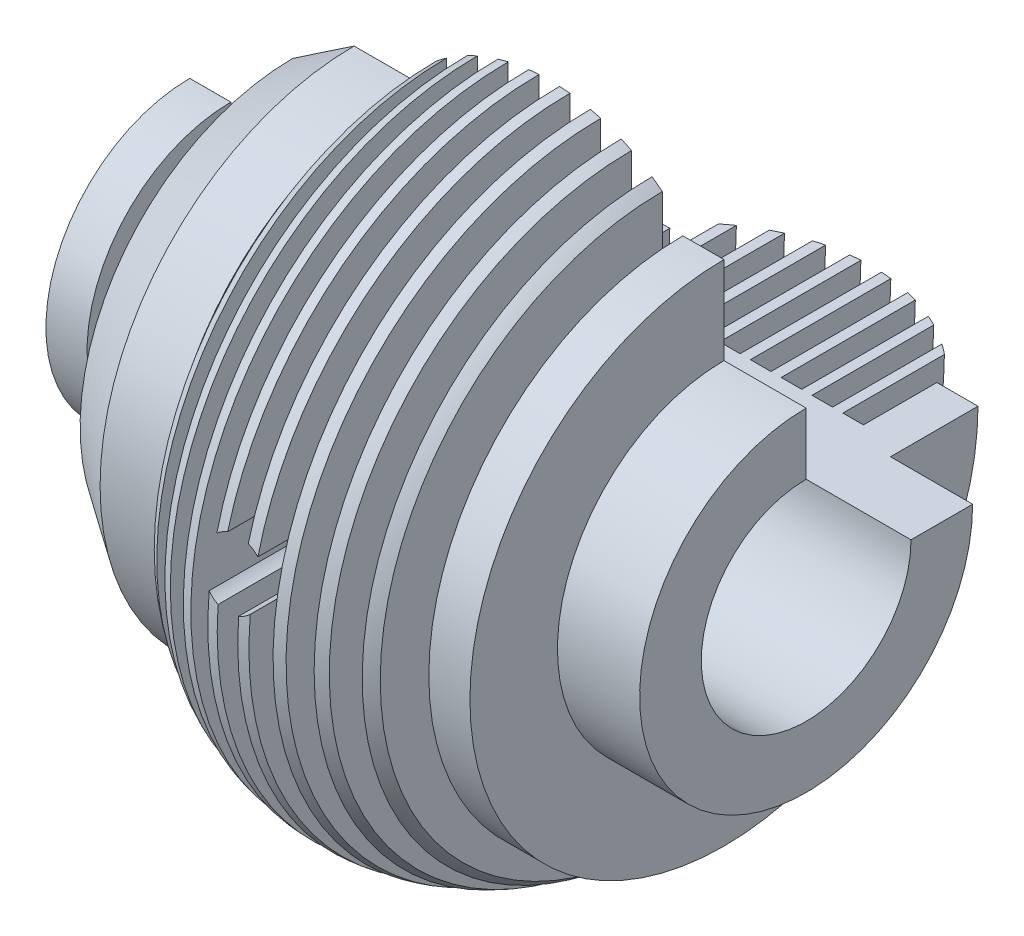
SolidWorks part; units mm, degrees
ref_plane "Front Plane" through (0, 0, 0) normal (0, 0, 1) x (1, 0, 0)
ref_plane "Top Plane" through (0, 0, 0) normal (0, 1, 0) x (1, 0, 0)
ref_plane "Right Plane" through (0, 0, 0) normal (1, 0, 0) x (0, 0, -1)
sketch "Sketch10" plane through (0, 0, 0) normal (0, 0, 1) x (1, 0, 0)
  line L0 (-146.8687, 1.7275) -> (-96.8687, 1.7275)
  line L1 (-96.8687, 1.7275) -> (-96.8687, 12.2465)
  line L2 (-96.8687, 12.2465) -> (3.1313, 12.2465)
  line L3 (3.1313, 12.2465) -> (3.1313, 27.2465)
  line L4 (3.1313, 27.2465) -> (-16.8687, 27.2465)
  line L5 (-16.8687, 27.2465) -> (-16.8687, 48.5465)
  line L6 (-16.8687, 48.5465) -> (-26.8687, 48.5465)
  line L7 (-26.8687, 48.5465) -> (-26.8687, 30.6645)
  line L8 (-26.8687, 30.6645) -> (-31.8687, 30.6645)
  line L9 (-91.8687, 30.6645) -> (-91.8687, 48.5465)
  line L10 (-91.8687, 48.5465) -> (-106.8687, 48.5465)
  line L11 (-106.8687, 48.5465) -> (-121.7914, 38.481)
  line L12 (-121.7914, 38.481) -> (-121.7914, 21.7275)
  line L13 (-131.7914, 11.7275) -> (-136.8687, 11.7275)
  line L14 (-136.8687, 11.7275) -> (-136.8687, 21.7275)
  line L15 (-136.8687, 21.7275) -> (-146.8687, 21.7275)
  line L16 (-146.8687, 21.7275) -> (-146.8687, 1.7275)
  line L17 (-146.8687, -13.2725) -> (-96.8687, -13.2725) construction
  line L18 (-86.8687, 30.6645) -> (-86.8687, 55.3695)
  line L19 (-84.3687, 30.6645) -> (-84.3687, 57.2522)
  line L20 (-86.8687, 30.6645) -> (-86.8687, 48.5465) construction
  line L21 (-84.3687, 30.6645) -> (-84.3687, 48.5465) construction
  line L22 (-79.3687, 30.6645) -> (-79.3687, 60.268)
  line L23 (-76.8687, 30.6645) -> (-76.8687, 61.4575)
  line L24 (-71.8687, 30.6645) -> (-71.8687, 63.2904)
  line L25 (-69.3687, 30.6645) -> (-69.3687, 63.9573)
  line L26 (-64.3687, 30.6645) -> (-64.3687, 64.8307)
  line L27 (-61.8687, 30.6645) -> (-61.8687, 65.0463)
  line L28 (-56.8687, 30.6645) -> (-56.8687, 65.0463)
  line L29 (-54.3687, 30.6645) -> (-54.3687, 64.8307)
  line L30 (-49.3687, 30.6645) -> (-49.3687, 63.9573)
  line L31 (-46.8687, 30.6645) -> (-46.8687, 63.2904)
  line L32 (-41.8687, 30.6645) -> (-41.8687, 61.4575)
  line L33 (-39.3687, 30.6645) -> (-39.3687, 60.268)
  line L34 (-34.3687, 30.6645) -> (-34.3687, 57.2522)
  line L35 (-31.8687, 30.6645) -> (-31.8687, 55.3695)
  line L36 (-86.8687, 30.6645) -> (-91.8687, 30.6645)
  line L37 (-79.3687, 30.6645) -> (-84.3687, 30.6645)
  line L38 (-71.8687, 30.6645) -> (-76.8687, 30.6645)
  line L39 (-64.3687, 30.6645) -> (-69.3687, 30.6645)
  line L40 (-56.8687, 30.6645) -> (-61.8687, 30.6645)
  line L41 (-49.3687, 30.6645) -> (-54.3687, 30.6645)
  line L42 (-41.8687, 30.6645) -> (-46.8687, 30.6645)
  line L43 (-34.3687, 30.6645) -> (-39.3687, 30.6645)
  arc A0 (-121.7914, 21.7275) -> (-131.7914, 11.7275) centre (-131.7914, 21.7275) cw
  arc A4 (-84.3687, 57.2522) -> (-86.8687, 55.3695) centre (-59.3687, 21.4555) ccw
  arc A5 (-76.8687, 61.4575) -> (-79.3687, 60.268) centre (-59.3687, 21.4555) ccw
  arc A6 (-69.3687, 63.9573) -> (-71.8687, 63.2904) centre (-59.3687, 21.4555) ccw
  arc A7 (-61.8687, 65.0463) -> (-64.3687, 64.8307) centre (-59.3687, 21.4555) ccw
  arc A8 (-54.3687, 64.8307) -> (-56.8687, 65.0463) centre (-59.3687, 21.4555) ccw
  arc A9 (-46.8687, 63.2904) -> (-49.3687, 63.9573) centre (-59.3687, 21.4555) ccw
  arc A10 (-39.3687, 60.268) -> (-41.8687, 61.4575) centre (-59.3687, 21.4555) ccw
  arc A11 (-31.8687, 55.3695) -> (-34.3687, 57.2522) centre (-59.3687, 21.4555) ccw
  point P16 (0, 0)
  dimension "D10" = 146
  dimension "D14" = 8
  dimension "D1" = 50
  dimension "D2" = 100
  dimension "D3" = 20
  dimension "D5" = 15
  dimension "D6" = 18
  dimension "D7" = 10
  dimension "D8" = 20
  dimension "D9" = 10
  dimension "D11" = 15
  dimension "D12" = 36.3
  dimension "D13" = 36.3
  dimension "D16" = 5
  dimension "D17" = 5
  dimension "D18" = 5
  dimension "D19" = 15
revolve "Revolve1" add sketch "Sketch10" angle 270 about L17
sketch "Sketch11" plane through (0, 0, 0) normal (0, 0, -1) x (-1, 0, 0)
  line L0 (61.8687, 30.6645) -> (61.8687, 65.0463) construction
  line L3 (131.7914, 11.7275) -> (136.8687, 11.7275) construction
  circle A0 centre (59.3687, -0.513) radius 7.5
  dimension "D1" = 15
  dimension "D2" = 75
  dimension "D3" = 2.5
  dimension "D4" = 53.3188
  dimension "D5" = 12.2405
extrude "Cut-Extrude1" cut sketch "Sketch11" against normal blind 103 contours A0
